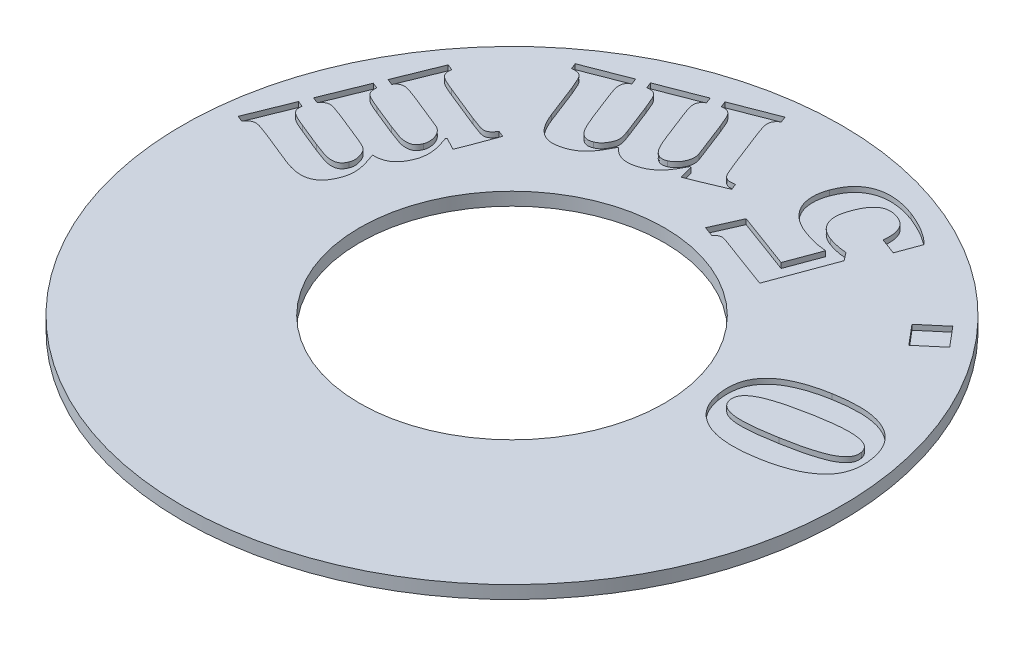
SolidWorks part; units mm, degrees
ref_plane "Front Plane" through (0, 0, 0) normal (0, 0, 1) x (1, 0, 0)
ref_plane "Top Plane" through (0, 0, 0) normal (0, 1, 0) x (1, 0, 0)
ref_plane "Right Plane" through (0, 0, 0) normal (1, 0, 0) x (0, 0, -1)
sketch "Sketch1" plane through (0, 0, 0) normal (0, 1, 0) x (1, 0, 0)
  circle A0 centre (0, 0) radius 12.7
  dimension "D1" = 25.4
extrude "Boss-Extrude1" add sketch "Sketch1" along normal blind 0.5
sketch "Sketch2" plane through (0, 0, 0) normal (0, -1, 0) x (-1, 0, 0)
  circle A0 centre (0, 0) radius 5.8674
  dimension "D1" = 11.7348
extrude "Cut-Extrude1" cut sketch "Sketch2" against normal through all
sketch "Sketch4" plane through (0, 0.5, 0) normal (0, 1, 0) x (1, 0, 0)
  circle A0 centre (0, 0) radius 12.0429 construction
  text T0 "<b>0.5mm</b>" font "Cambria" height 5.08
extrude "Cut-Extrude2" cut sketch "Sketch4" against normal blind 0.2
